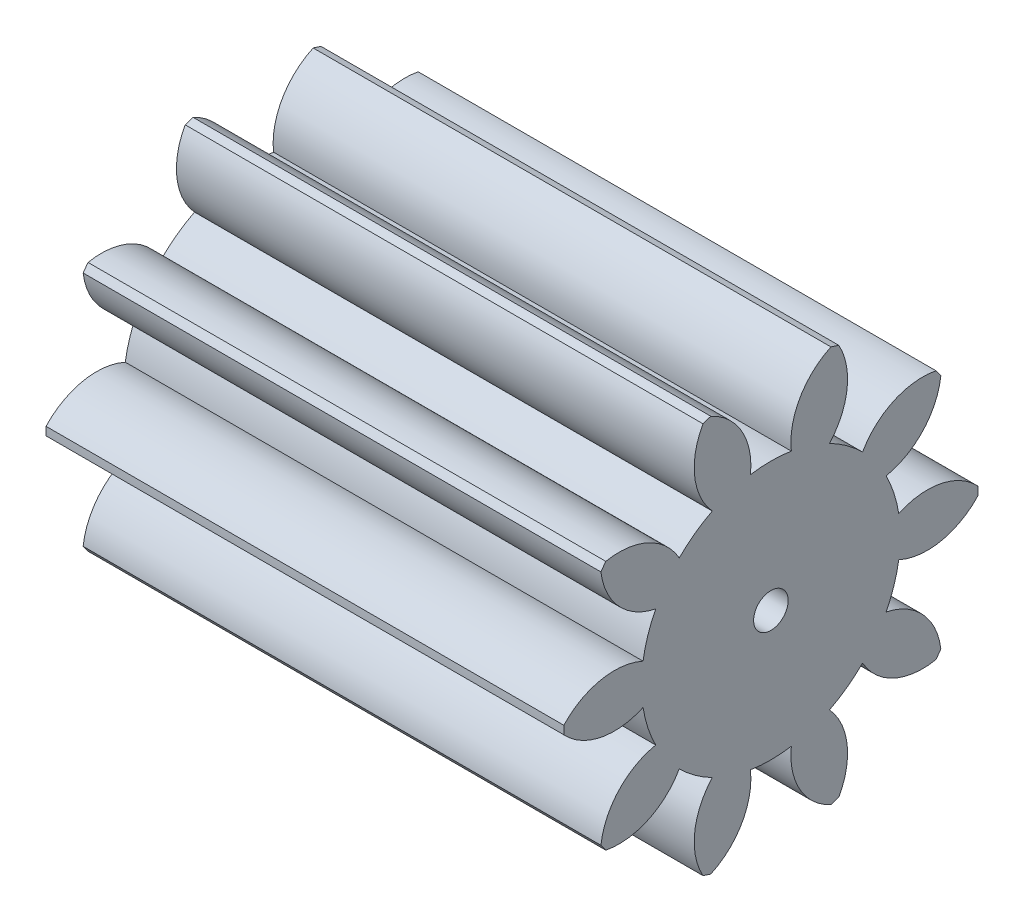
SolidWorks part; units mm, degrees
ref_plane "Plane1" through (0, 0, 0) normal (0, 0, 1) x (1, 0, 0)
ref_plane "Plane2" through (0, 0, 0) normal (0, 1, 0) x (1, 0, 0)
ref_plane "Plane3" through (0, 0, 0) normal (1, 0, 0) x (0, 0, -1)
other "Configuration Table"
sketch "HoldingSke" plane through (0, 0, 0) normal (0, 1, 0) x (1, 0, 0)
  line L0 (0, 0) -> (1.231, -0.2171)
  line L1 (-15, 0) -> (100, 0) construction
  line L2 (0, 0) -> (-2.1039, 2.3779)
  line L3 (0, 0) -> (-11.863, 4.5341)
  line L4 (0, 0) -> (8.5048, 1.4996)
  line L5 (0, 0) -> (-46.8476, -17.4728)
  line L6 (0, 0) -> (-9.9476, -6.7116)
  line L7 (-2.1039, 2.3779) -> (8.6586, 51.2059)
  line L8 (-76.2, 54.61) -> (-76.1, 54.61)
  line L9 (-71.009, 38.7566) -> (-53.1078, 45.2721)
  line L10 (-76.2, 71.12) -> (104.1128, 71.12)
  line L11 (0, 0) -> (-12, 0)
  line L12 (-76.2, 101.6) -> (-76.17, 101.6)
  line L13 (24.9733, 27.94) -> (52.9518, 28.4284)
  line L14 (24.9733, 27.94) -> (24.9743, 27.94)
  line L15 (24.9733, 27.94) -> (100.4006, 29.5858)
  line L16 (-63.627, -0.8) -> (-12.827, -0.8)
  circle A0 centre (0, 0) radius 0.4
  circle A1 centre (0, 0) radius 2.999
  circle A2 centre (0, 0) radius 37.5
  circle A3 centre (0, 0) radius 0.4
  dimension "MHD" = 5.998
  dimension "Hub_dia" = 75
  dimension "Bore" = 0.8
  dimension "MBD" = 0.8
  dimension "Num_teeth" = 10
  dimension "Pitch" = 1.25
  dimension "Overall_len" = 50
  dimension "Show_teeth" = 10
  dimension "Thickness" = 12
  dimension "OAL" = 50.0001
  dimension "T_dim" = 0.1
  dimension "Ap" = 20
  dimension "H" = 19.05
  dimension "Pitch_radius" = 180.3128
  dimension "Width" = 12
  dimension "Backlash" = 0.03
  dimension "Addendum_fac" = 1
  dimension "Dedendum_fac" = 1.25
  dimension "Clearance_fac" = 0.25
  dimension "Dedendum_add" = 0.001
  dimension "Module" = 0.8
sketch "BasProSke" plane through (0, 0, 0) normal (0, 1, 0) x (1, 0, 0)
  line L0 (-10, 0) -> (60, 0) construction
  line L1 (0, 0) -> (0, 4.8)
  line L2 (0, 0) -> (12, 0)
  line L3 (12, 0) -> (12, 4.8)
  line L4 (12, 4.8) -> (0, 4.8)
  dimension "Thickness" = 12
  dimension "Diameter" = 9.6
revolve "Base-Revolve" add sketch "BasProSke" angle 360 about L0
sketch "TooCutSke" plane through (0, 0, 0) normal (1, 0, 0) x (0, 0, -1)
  line L1 (0, 0) -> (0, 107) construction
  line L2 (0, 0) -> (-0.6781, 3.9421) construction
  line L3 (0, 0) -> (-2.4466, 7.5299) construction
  line L4 (-0.6781, 3.9421) -> (-1.2233, 3.765) construction
  arc A0 (0.4737, 2.9613) -> (-0.4737, 2.9613) centre (0, 0) ccw
  arc A1 (1.4269, 4.6096) -> (-1.4269, 4.6096) centre (0, 0) ccw
  circle A2 centre (0, 0) radius 4 construction
  circle A3 centre (0, 0) radius 3.7588 construction
  arc A4 (-0.4737, 2.9613) -> (-1.4269, 4.6096) centre (-2.0635, 3.1417) ccw
  arc A5 (1.4269, 4.6096) -> (0.4737, 2.9613) centre (2.0635, 3.1417) ccw
  dimension "Root_dia" = 5.998
  dimension "Overcut_dia" = 9.6508
  dimension "Pitch_dia" = 8
  dimension "Base_dia" = 7.5175
  dimension "Flank_rad" = 1.6
  dimension "Half_ang" = 18
  dimension "Half_CT" = 0.5732
extrude "ToothCut" cut sketch "TooCutSke" along normal through all
fillet "Breaks" [suppressed] radius 0.016
fillet "RootFillets" [suppressed] radius 0.201
pattern_circular "TeethCuts" count 10 every 36 about axis through (-10, 0, 0) along (1, 0, 0) of "ToothCut", "RootFillets", "Breaks"
sketch "HubNeaOneSke" plane through (0, 0, 0) normal (-1, 0, 0) x (0, 0, 1)
  circle A0 centre (0, 0) radius 2.999
  dimension "Diameter" = 5.998
extrude "HubNearOne" [suppressed] add sketch "HubNeaOneSke" along normal blind 38.0001
sketch "HubNeaBotSke" plane through (0, 0, 0) normal (-1, 0, 0) x (0, 0, 1)
  circle A0 centre (0, 0) radius 2.999
  dimension "Diameter" = 5.998
extrude "HubNearBoth" [suppressed] add sketch "HubNeaBotSke" along normal blind 19
ref_plane "FarPln" through (12, 0, 0) normal (1, 0, 0) x (0, 0, -1)
sketch "HubFarSke" plane through (12, 0, 0) normal (1, 0, 0) x (0, 0, -1)
  circle A0 centre (0, 0) radius 2.999
  dimension "Diameter" = 5.998
extrude "HubFar" [suppressed] add sketch "HubFarSke" along normal blind 19
sketch "BorSke" plane through (0, 0, 0) normal (1, 0, 0) x (0, 0, -1)
  circle A0 centre (0, 0) radius 0.4
  dimension "Diameter" = 0.8
extrude "Bore" cut sketch "BorSke" along normal mid plane 100.0001
sketch "KeySke" plane through (0, 0, 0) normal (1, 0, 0) x (0, 0, -1)
  line L0 (-0.05, 0) -> (-0.05, 0.5)
  line L1 (-0.05, 0.5) -> (0.05, 0.5)
  line L2 (0.05, 0.5) -> (0.05, 0)
  line L3 (0, 0) -> (0, 34) construction
  line L4 (-0.05, 0) -> (0.05, 0)
  dimension "Offset" = 0.5
  dimension "Width" = 0.1
extrude "Keyway" [suppressed] cut sketch "KeySke" along normal mid plane 100.0001
pattern_circular "Keyway2" [suppressed] count 2 every 90 about axis through (-10, 0, 0) along (1, 0, 0)
equation "' \"Module@HoldingSke\" = 6.35"
equation "' \"Num_teeth@HoldingSke\" = 12"
equation "' \"Ap@HoldingSke\" =  20"
equation "' \"Ap@HoldingSke\" = 20"
equation "' \"Width@HoldingSke\" = 0.5 * 25.4"
equation "' \"Hub_dia@HoldingSke\"= 1 * 25.4"
equation "' \"Hub_dia@HoldingSke\" = 1 * 25.4"
equation "' \"Overall_len@HoldingSke\" = 1.0 * 25.4"
equation "' \"Bore@HoldingSke\" = 0.75 * 25.4"
equation "' \"T_dim@HoldingSke\" = 0.1 * 25.4"
equation "' \"Width@KeySke\" = 0.25 * 25.4"
equation "' \"Show_teeth@HoldingSke\" = 13"
equation "' \"Backlash@HoldingSke\" = 0.009 * 25.4"
equation "' \"Addendum_fac@HoldingSke\" = 1.0"
equation "' \"Dedendum_fac@HoldingSke\" = 1.25"
equation "' \"Dedendum_add@HoldingSke\" = 0.00005 * 25.4"
equation "' \"Clearance_fac@HoldingSke\" = 0.25"
equation "\"Pitch@HoldingSke\" = 1 / \"Module@HoldingSke\""
equation "\"Overcut_dia@TooCutSke\" = (\"Num_teeth@HoldingSke\" + 2 * \"Addendum_fac@HoldingSke\") / \"Pitch@HoldingSke\" + 0.002 * 25.4"
equation "\"Pitch_dia@TooCutSke\" = \"Num_teeth@HoldingSke\" / \"Pitch@HoldingSke\""
equation "\"Base_dia@TooCutSke\" = \"Num_teeth@HoldingSke\" / \"Pitch@HoldingSke\" * cos((\"Ap@HoldingSke\"  * 3.14159265 / 180))"
equation "\"Root_dia@TooCutSke\" = (\"Num_teeth@HoldingSke\" + 2) / \"Pitch@HoldingSke\" - 2 * (\"Addendum_fac@HoldingSke\" + \"Dedendum_fac@HoldingSke\") / \"Pitch@HoldingSke\" - \"Dedendum_add@HoldingSke\" * 2"
equation "\"Half_ang@TooCutSke\" = 180 / \"Num_teeth@HoldingSke\""
equation "\"Half_CT@TooCutSke\" = \"Num_teeth@HoldingSke\" / \"Pitch@HoldingSke\" * sin((3.14159265 / 2 / \"Num_teeth@HoldingSke\")) / 2 - 7 * \"Backlash@HoldingSke\" / 4"
equation "\"Flank_rad@TooCutSke\" = \"Num_teeth@HoldingSke\" / \"Pitch@HoldingSke\" / 5"
equation "\"Radius@RootFillets\" = \"Clearance_fac@HoldingSke\" / \"Pitch@HoldingSke\" + \"Dedendum_add@HoldingSke\""
equation "\"Break_rad@Breaks\" = 0.02 / \"Pitch@HoldingSke\""
equation "\"Thickness@HoldingSke\" = \"Width@HoldingSke\""
equation "\"OAL@HoldingSke\" = \"Thickness@HoldingSke\""
equation "\"MHD@HoldingSke\" = (\"Num_teeth@HoldingSke\" + 2) / \"Pitch@HoldingSke\" - 2 * (\"Addendum_fac@HoldingSke\" + \"Dedendum_fac@HoldingSke\")  / \"Pitch@HoldingSke\" - \"Dedendum_add@HoldingSke\" * 2"
equation "\"MBD@HoldingSke\" = (\"Num_teeth@HoldingSke\" + 2) / \"Pitch@HoldingSke\" - 2 * (\"Addendum_fac@HoldingSke\" + \"Dedendum_fac@HoldingSke\")  / \"Pitch@HoldingSke\" - \"Dedendum_add@HoldingSke\" * 2 - 0.002 * 25.4"
equation "\"MHD@HoldingSke\" = ((sgn( \"MHD@HoldingSke\" - \"Hub_dia@HoldingSke\" )-1)*( \"MHD@HoldingSke\" - \"Hub_dia@HoldingSke\" ))/-2+ \"Hub_dia@HoldingSke\""
equation "\"MBD@HoldingSke\" = ((sgn( \"MBD@HoldingSke\" - \"Bore@HoldingSke\" )-1)*( \"MBD@HoldingSke\" - \"Bore@HoldingSke\" ))/-2+ \"Bore@HoldingSke\""
equation "\"OAL@HoldingSke\" = ((sgn( \"OAL@HoldingSke\" - \"Overall_len@HoldingSke\" )+1)*( \"OAL@HoldingSke\" - \"Overall_len@HoldingSke\" ))/2 + \"Overall_len@HoldingSke\" + 0.000002 * 25.4"
equation "\"Num_teeth@TeethCuts\" = int( \"Show_teeth@HoldingSke\" ) + 1"
equation "\"Num_teeth@TeethCuts\" = ((sgn( \"Num_teeth@TeethCuts\" - \"Num_teeth@HoldingSke\" )-1)*( \"Num_teeth@TeethCuts\" - \"Num_teeth@HoldingSke\" ))/-2+ \"Num_teeth@HoldingSke\""
equation "\"Num_teeth@TeethCuts\" = ((sgn( \"Num_teeth@TeethCuts\" - 2.0)+1)*( \"Num_teeth@TeethCuts\" - 2.0))/2 +2.0"
equation "\"Angle@TeethCuts\" = 360.0 / \"Num_teeth@HoldingSke\""
equation "\"Diameter@BasProSke\" = (\"Num_teeth@HoldingSke\" + 2 * \"Addendum_fac@HoldingSke\") / \"Pitch@HoldingSke\""
equation "\"Thickness@BasProSke\"  = \"Thickness@HoldingSke\""
equation "' \"Fillet_rad@BasProSke\" =  \"Thickness@HoldingSke\" * 0.05"
equation "' \"Fillet_rad@BasProSke\" = \"Thickness@HoldingSke\" * 0.05"
equation "\"MHD@HoldingSke\" = ((sgn( \"MHD@HoldingSke\" - \"Root_dia@TooCutSke\" )-1)*( \"MHD@HoldingSke\" - \"Root_dia@TooCutSke\" ))/-2+ \"Root_dia@TooCutSke\""
equation "\"Diameter@HubNeaOneSke\" = \"MHD@HoldingSke\""
equation "\"Length@HubNearOne\" = \"OAL@HoldingSke\" - \"Thickness@BasProSke\""
equation "\"Diameter@HubNeaBotSke\" = \"MHD@HoldingSke\""
equation "\"Length@HubNearBoth\" = ( \"OAL@HoldingSke\" - \"Thickness@BasProSke\" ) / 2.0"
equation "\"Thickness@FarPln\" = \"Thickness@BasProSke\""
equation "\"Diameter@HubFarSke\" = \"MHD@HoldingSke\""
equation "\"Length@HubFar\" = ( \"OAL@HoldingSke\" - \"Thickness@BasProSke\" ) / 2.0"
equation "\"Diameter@BorSke\" = \"MBD@HoldingSke\""
equation "\"D1@Bore\" = \"OAL@HoldingSke\" * 2.0"
equation "\"D1@Keyway\" = \"OAL@HoldingSke\" * 2.0"
equation "\"Offset@KeySke\" = \"T_dim@HoldingSke\" + \"MBD@HoldingSke\" / 2.0"
